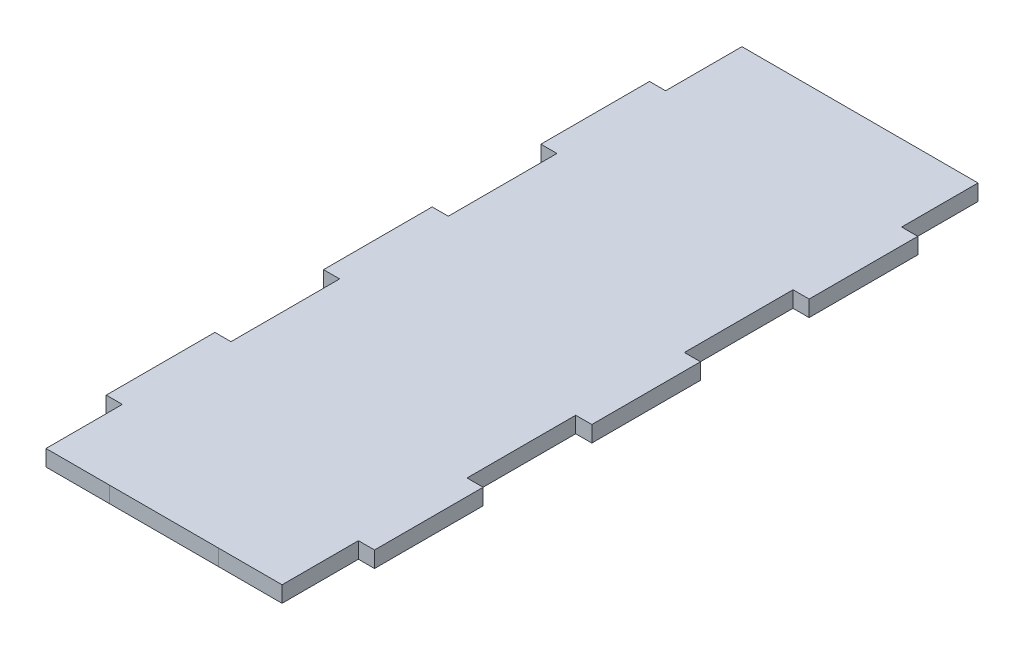
SolidWorks part; units mm, degrees
ref_plane "Front Plane" through (0, 0, 0) normal (0, 0, 1) x (1, 0, 0)
ref_plane "Top Plane" through (0, 0, 0) normal (0, 1, 0) x (1, 0, 0)
ref_plane "Right Plane" through (0, 0, 0) normal (1, 0, 0) x (0, 0, -1)
sketch "Sketch1" plane through (0, 0, 0) normal (0, 1, 0) x (1, 0, 0)
  line L1 (258.9423, 153.7725) -> (-258.9423, 153.7725)
  line L2 (258.9423, 153.7725) -> (258.9423, -153.7725)
  line L3 (258.9423, -153.7725) -> (-258.9423, -153.7725)
  line L4 (-258.9423, 153.7725) -> (-258.9423, -153.7725)
  line L5 (258.9423, 153.7725) -> (-258.9423, -153.7725) construction
  line L6 (258.9423, -153.7725) -> (-258.9423, 153.7725) construction
  point P0 (0, 0)
extrude "Boss-Extrude1" add sketch "Sketch1" along normal blind 6
sketch "Sketch2" plane through (0, 6, 0) normal (0, 1, 0) x (1, 0, 0)
  line B0 (38.8921, -123.8157) -> (38.8921, -95.3595)
  line B1 (38.8921, -95.3595) -> (44.8921, -95.3595)
  line B2 (44.8921, -95.3595) -> (44.8921, -54.8595)
  line B3 (44.8921, -54.8595) -> (38.8921, -54.8595)
  line B4 (38.8921, -54.8595) -> (38.8921, -14.3595)
  line B5 (38.8921, -14.3595) -> (44.8921, -14.3595)
  line B6 (44.8921, -14.3595) -> (44.8921, 26.1405)
  line B7 (44.8921, 26.1405) -> (38.8921, 26.1405)
  line B8 (38.8921, 26.1405) -> (38.8921, 66.6405)
  line B9 (38.8921, 66.6405) -> (44.8921, 66.6405)
  line B10 (44.8921, 66.6405) -> (44.8921, 107.1405)
  line B11 (44.8921, 107.1405) -> (38.8921, 107.1405)
  line B12 (38.8921, 107.1405) -> (38.8921, 135.5972)
  line B13 (38.8921, 135.5972) -> (15.1421, 135.5972)
  line B14 (15.1421, 135.5972) -> (15.1421, 135.5955)
  line B15 (15.1421, 135.5955) -> (-25.3579, 135.5955)
  line B16 (-25.3579, 135.5955) -> (-25.3579, 135.5972)
  line B17 (-25.3579, 135.5972) -> (-49.1079, 135.5972)
  line B18 (-49.1079, 135.5972) -> (-49.1079, 107.1405)
  line B19 (-49.1079, 107.1405) -> (-55.1079, 107.1405)
  line B20 (-55.1079, 107.1405) -> (-55.1079, 66.6405)
  line B21 (-55.1079, 66.6405) -> (-49.1079, 66.6405)
  line B22 (-49.1079, 66.6405) -> (-49.1079, 26.1405)
  line B23 (-49.1079, 26.1405) -> (-55.1079, 26.1405)
  line B24 (-55.1079, 26.1405) -> (-55.1079, -14.3595)
  line B25 (-55.1079, -14.3595) -> (-49.1079, -14.3595)
  line B26 (-49.1079, -14.3595) -> (-49.1079, -54.8595)
  line B27 (-49.1079, -54.8595) -> (-55.1079, -54.8595)
  line B28 (-55.1079, -54.8595) -> (-55.1079, -95.3595)
  line B29 (-55.1079, -95.3595) -> (-49.1079, -95.3595)
  line B30 (-49.1079, -95.3595) -> (-49.1079, -123.8157)
  line B31 (-49.1079, -123.8157) -> (-25.3579, -123.8157)
  line B32 (-25.3579, -123.8157) -> (-25.3579, -123.8145)
  line B33 (-25.3579, -123.8145) -> (15.1421, -123.8145)
  line B34 (15.1421, -123.8145) -> (15.1421, -123.8157)
  line B35 (15.1421, -123.8157) -> (38.8921, -123.8157)
sketch_block_instance "Block1-1"
sketch_block "Block1"
extrude "Cut-Extrude-Thin1" cut sketch "Sketch2" against normal through all thin thin type mid plane wall 0.01
